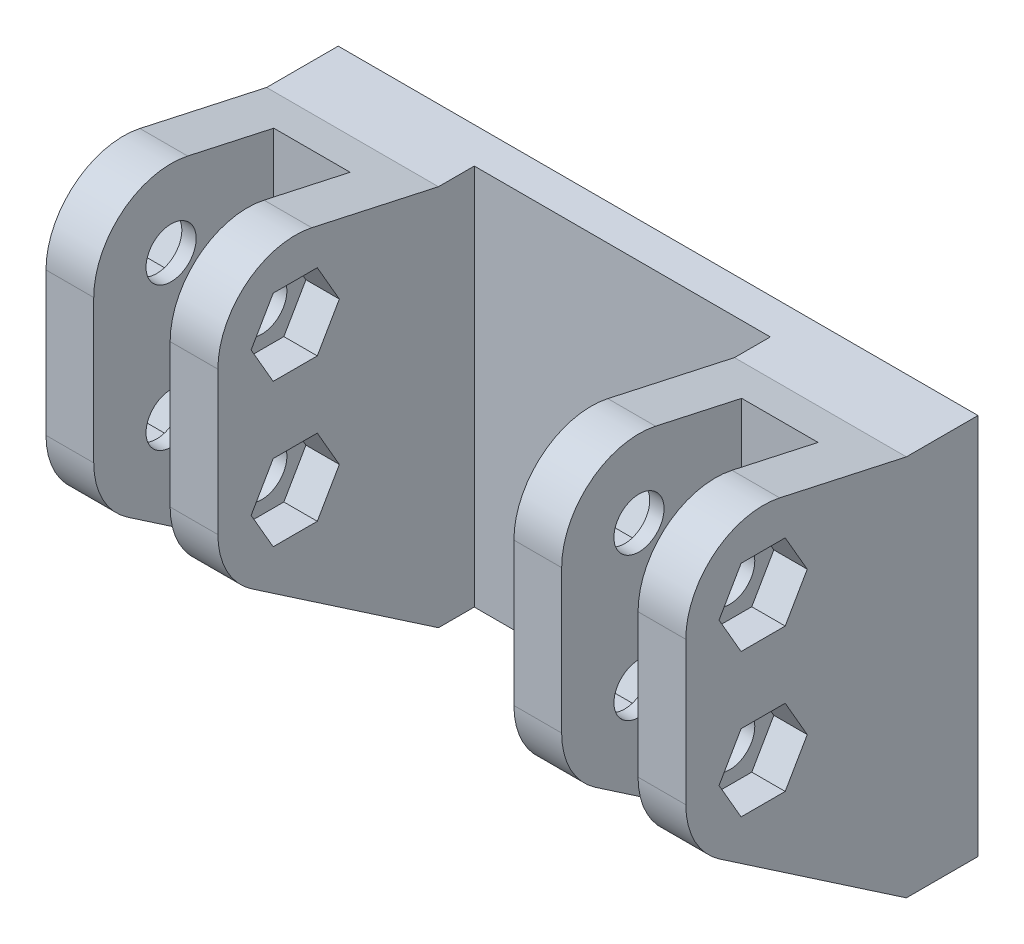
SolidWorks part; units mm, degrees
material "ABS"
ref_plane "Front Plane" through (0, 0, 0) normal (0, 0, 1) x (1, 0, 0)
ref_plane "Top Plane" through (0, 0, 0) normal (0, 1, 0) x (1, 0, 0)
ref_plane "Right Plane" through (0, 0, 0) normal (1, 0, 0) x (0, 0, -1)
sketch "Sketch1" plane through (0, 0, 0) normal (1, 0, 0) x (0, 0, -1)
  line L0 (0, 40) -> (0, 0) construction
  line L1 (0, 0) -> (5, 0)
  line L3 (0, 40) -> (5, 40)
  line L4 (5, 0) -> (5, 40)
  line L5 (0, 40) -> (-2.5, 40)
  line L7 (0, 0) -> (-2.5, 0)
  line L8 (-2.5, 40) -> (-2.5, 0) construction
  line L9 (-25.6, 35) -> (-25.6, 20)
  line L10 (-2.5, 0) -> (-22.0558, 13.3026)
  line L11 (-2.5, 40) -> (-15.7632, 42.9116)
  circle A0 centre (-17.5, 35) radius 2.625
  arc A1 (-15.7632, 42.9116) -> (-25.6, 35) centre (-17.5, 35) ccw
  circle A2 centre (-17.5, 20) radius 2.625
  arc A3 (-25.6, 20) -> (-22.0558, 13.3026) centre (-17.5, 20) ccw
  point P7 (-17.5, 20)
  point P8 (-17.5, 35)
  dimension "D7" = 5.25
  dimension "D8" = 8.1
  dimension "D9" = 5.25
  dimension "D10" = 8.1
  dimension "D1" = 5
  dimension "D2" = 2.5
  dimension "D3" = 40
  dimension "D4" = 15
  dimension "D5" = 20
  dimension "D6" = 15
extrude "Boss-Extrude1" add sketch "Sketch1" along normal blind 18
sketch "Sketch2" plane through (0, 0, 0) normal (-1, 0, 0) x (0, 0, 1)
  line L0 (-5, 40) -> (2.5, 40) construction
  line L1 (-5, 0) -> (-1.25, 0)
  line L2 (-5, 0) -> (-5, 40)
  line L3 (-5, 40) -> (-1.25, 40)
  line L4 (-1.25, 0) -> (-1.25, 40)
extrude "Boss-Extrude2" add sketch "Sketch2" along normal blind 15.5
sketch "Sketch3" plane through (18, 0, 0) normal (1, 0, 0) x (0, 0, -1)
  line L1 (-12.8812, 35) -> (-15.1906, 39)
  line L2 (-15.1906, 39) -> (-19.8094, 39)
  line L3 (-19.8094, 39) -> (-22.1188, 35)
  line L4 (-22.1188, 35) -> (-19.8094, 31)
  line L5 (-19.8094, 31) -> (-15.1906, 31)
  line L6 (-15.1906, 31) -> (-12.8812, 35)
  line L7 (-12.8812, 20) -> (-15.1906, 24)
  line L8 (-15.1906, 24) -> (-19.8094, 24)
  line L9 (-19.8094, 24) -> (-22.1188, 20)
  line L10 (-22.1188, 20) -> (-19.8094, 16)
  line L11 (-19.8094, 16) -> (-15.1906, 16)
  line L12 (-15.1906, 16) -> (-12.8812, 20)
  circle A0 centre (-17.5, 35) radius 3.1 construction
  circle A1 centre (-17.5, 35) radius 4 construction
  circle A2 centre (-17.5, 20) radius 4 construction
  dimension "D1" = 8
  dimension "D2" = 8
extrude "Cut-Extrude1" cut sketch "Sketch3" against normal blind 3.5
ref_plane "Plane1" through (9, 0, 0) normal (1, 0, 0) x (0, 0, -1)
mirror "Mirror1" about plane through (9, 0, 0) normal (1, 0, 0) of "Cut-Extrude1"
sketch "Sketch4" plane through (9, 0, 0) normal (1, 0, 0) x (0, 0, -1)
  line L0 (1.25, 0) -> (1.25, 40) construction
  line L1 (-6.75, 43.493) -> (-32.9351, 43.493)
  line L2 (-6.75, 43.493) -> (-6.75, 0)
  line L3 (-6.75, 0) -> (-32.9351, 0)
  line L4 (-32.9351, 43.493) -> (-32.9351, 0)
  dimension "D1" = 8
extrude "Cut-Extrude2" cut sketch "Sketch4" against normal blind 4 and the other way blind 4
sketch "Sketch5" plane through (0, 0, -1.25) normal (0, 0, 1) x (1, 0, 0)
  line L0 (-15.5, 40) -> (-15.5, 0) construction
  line L1 (-15.5, 23.302) -> (-15.5, 16.698)
  arc A0 (-15.5, 16.698) -> (-15.5, 23.302) centre (-15.5, 20) ccw
  dimension "D1" = 6.604
extrude "Cut-Extrude3" cut sketch "Sketch5" against normal up to surface (3.75 mm away) up to face at (1.25, 20, -5)
mirror "Mirror2" about plane through (-15.5, 0, 0) normal (1, 0, 0) of bodies 106
